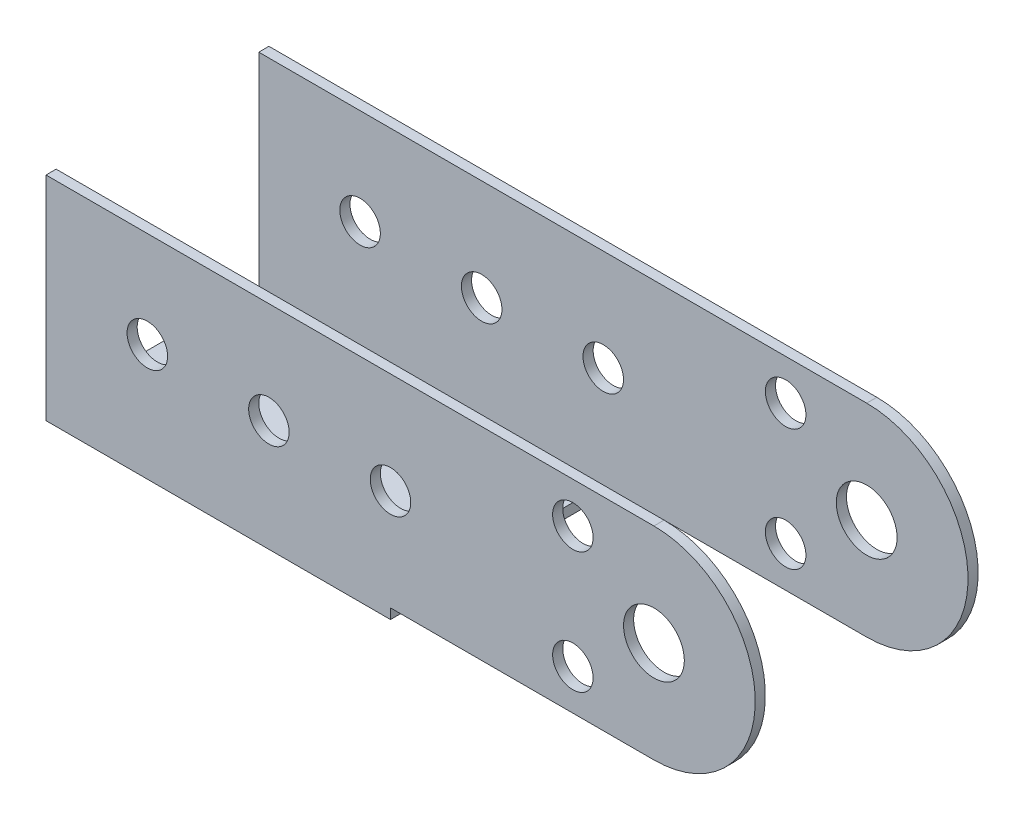
SolidWorks part; units mm, degrees
ref_plane "前视" through (0, 0, 0) normal (0, 0, 1) x (1, 0, 0)
ref_plane "上视" through (0, 0, 0) normal (0, 1, 0) x (1, 0, 0)
ref_plane "右视" through (0, 0, 0) normal (1, 0, 0) x (0, 0, -1)
sketch "草图1" plane through (0, 0, 0) normal (0, 0, 1) x (1, 0, 0)
  line L0 (-10, 13.6585) -> (-10, -13.1517) construction
  line L1 (-15, 5) -> (15, 5)
  line L2 (-15, 5) -> (-15, -5)
  line L3 (-15, -5) -> (15, -5)
  line L4 (-16.7978, 0) -> (28.1127, 0) construction
  line L5 (11, 8.6867) -> (11, -8.5755) construction
  line L7 (-4, 13.6585) -> (-4, -13.1517) construction
  line L8 (2, 13.6585) -> (2, -13.1517) construction
  arc A0 (15, -5) -> (15, 5) centre (15, 0) ccw
  circle A1 centre (15, 0) radius 1.5
  circle A2 centre (-10, 0.2534) radius 1
  circle A3 centre (-4, 0) radius 1
  circle A4 centre (2, 0) radius 1
  circle A5 centre (11, 3) radius 1
  circle A6 centre (11, -3) radius 1
  point P0 (0, 0)
  dimension "D3" = 10
  dimension "D4" = 3
  dimension "D8" = 2
  dimension "D9" = 2
  dimension "D10" = 2
  dimension "D14" = 2
  dimension "D15" = 2
  dimension "D1" = 10
  dimension "D2" = 30
  dimension "D5" = 5
  dimension "D6" = 11
  dimension "D7" = 17
  dimension "D11" = 3
  dimension "D12" = 3
  dimension "D13" = 4
ref_plane "基准面1" through (0, 0, 10) normal (0, 0, 1) x (1, 0, 0)
sketch "草图2" plane through (0, 0, 10) normal (0, 0, 1) x (1, 0, 0)
  line L3 (15, 5) -> (-15, 5)
  line L4 (-15, -5) -> (15, -5)
  line L5 (-15, 5) -> (-15, -5)
  line L6 (15, 5) -> (-15, 5)
  line L7 (-15, -5) -> (15, -5)
  line L8 (-15, 5) -> (-15, -5)
  circle A1 centre (15, 0) radius 1.5
  circle A2 centre (15, 0) radius 1.5
  arc A3 (15, -5) -> (15, 5) centre (15, 0) ccw
  arc A4 (15, -5) -> (15, 5) centre (15, 0) ccw
  circle A5 centre (11, -3) radius 1
  circle A6 centre (11, -3) radius 1
  circle A7 centre (11, 3) radius 1
  circle A8 centre (11, 3) radius 1
  circle A9 centre (2, 0) radius 1
  circle A10 centre (2, 0) radius 1
  circle A11 centre (-4, 0) radius 1
  circle A12 centre (-4, 0) radius 1
  circle A13 centre (-10, 0.2534) radius 1
  circle A14 centre (-10, 0.2534) radius 1
  dimension "D1" = 0
  dimension "D2" = 0
  dimension "D3" = 0
  dimension "D4" = 0
  dimension "D5" = 0
  dimension "D6" = 0
  dimension "D7" = 0
extrude "凸台-拉伸1" add sketch "草图2" along normal blind 0.5
extrude "凸台-拉伸2" add sketch "草图1" against normal blind 0.5 separate body
ref_plane "基准面2" through (0, -5, 0) normal (0, 1, 0) x (1, 0, 0)
sketch "草图4" plane through (0, -5, 0) normal (0, 1, 0) x (1, 0, 0)
  line L0 (-15, 0.5) -> (2, 0.5)
  line L1 (-15, 0.5) -> (-15, 0) construction
  line L2 (2, 0.5) -> (2, 0) construction
  line L3 (2, 0.5) -> (2, -10.5)
  line L4 (2, -10.5) -> (2, -10) construction
  line L5 (15, -10.5) -> (-15, -10.5) construction
  line L6 (2, -10.5) -> (-15, -10.5)
  line L7 (-15, -10.5) -> (-15, 0.5)
extrude "凸台-拉伸4" add sketch "草图4" against normal blind 0.5
